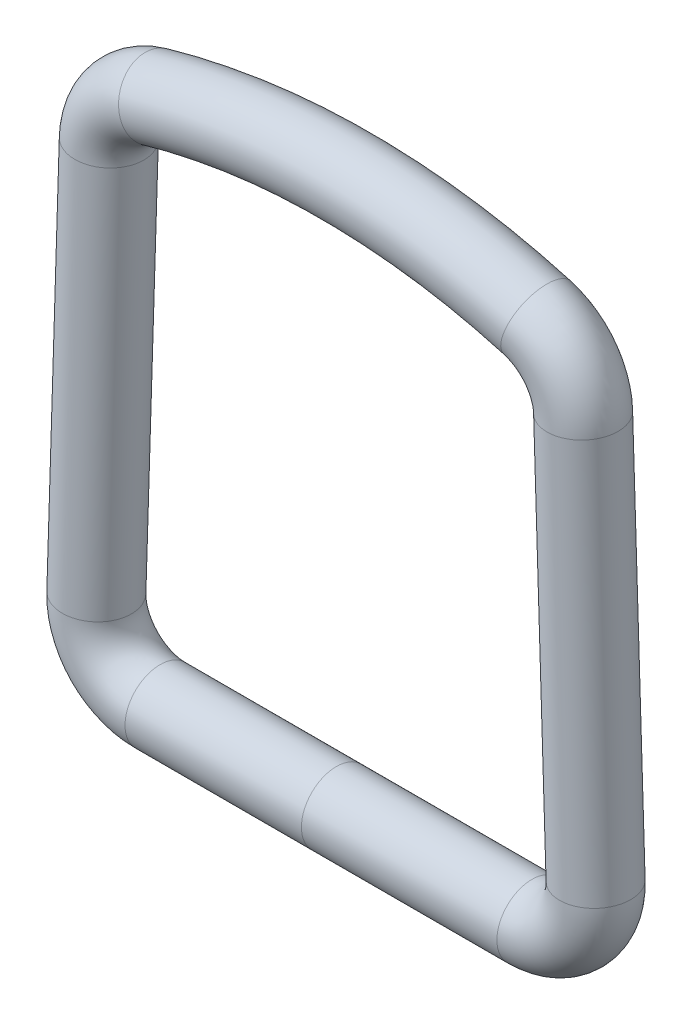
SolidWorks part; units mm, degrees
material "合金钢"
ref_plane "前视基准面" through (0, 0, 0) normal (0, 0, 1) x (1, 0, 0)
ref_plane "上视基准面" through (0, 0, 0) normal (0, 1, 0) x (1, 0, 0)
ref_plane "右视基准面" through (0, 0, 0) normal (1, 0, 0) x (0, 0, -1)
sketch "草图1" plane through (0, 0, 0) normal (0, 0, 1) x (1, 0, 0)
  line L4 (2.0635, 0) -> (13.7365, 0)
  line L5 (15.7355, 2.0625) -> (15.3439, 14.5955)
  line L6 (15.3, 16) -> (0.5, 16) construction
  line L7 (0.4561, 14.5955) -> (0.0645, 2.0625)
  line L8 (7.9, 16) -> (7.9, 0) construction
  line L9 (7.9, 16) -> (7.9, 17.3) construction
  arc A5 (13.8973, 16.4553) -> (1.9027, 16.4553) centre (7.9, -4.4115) ccw
  arc A6 (13.7365, 0) -> (15.7355, 2.0625) centre (13.7365, 2) ccw
  arc A7 (2.0635, 0) -> (0.0645, 2.0625) centre (2.0635, 2) cw
  arc A8 (15.3439, 14.5955) -> (13.8973, 16.4553) centre (13.3449, 14.5331) ccw
  arc A9 (1.9027, 16.4553) -> (0.4561, 14.5955) centre (2.4551, 14.5331) ccw
  point P10 (15.8, 0)
  point P14 (0, 0)
  dimension "D2" = 14.8
  dimension "D3" = 16
  dimension "D4" = 17.3
  dimension "D5" = 2
  dimension "D1" = 15.8
ref_plane "基准面1" through (7.6, 0, 0) normal (1, 0, 0) x (0, 0, -1)
sketch "草图3" plane through (7.6, 0, 0) normal (1, 0, 0) x (0, 0, -1)
  circle A0 centre (0, 0) radius 1.1
  dimension "D1" = 2.2
sweep "扫描1" add profiles "草图3" path "草图1"
sketch "草图4" plane through (7.6, 0, 0) normal (1, 0, 0) x (0, 0, -1)
  circle A1 centre (0, 17.3) radius 1.5
  dimension "D1" = 3
  dimension "D2" = 17.3
